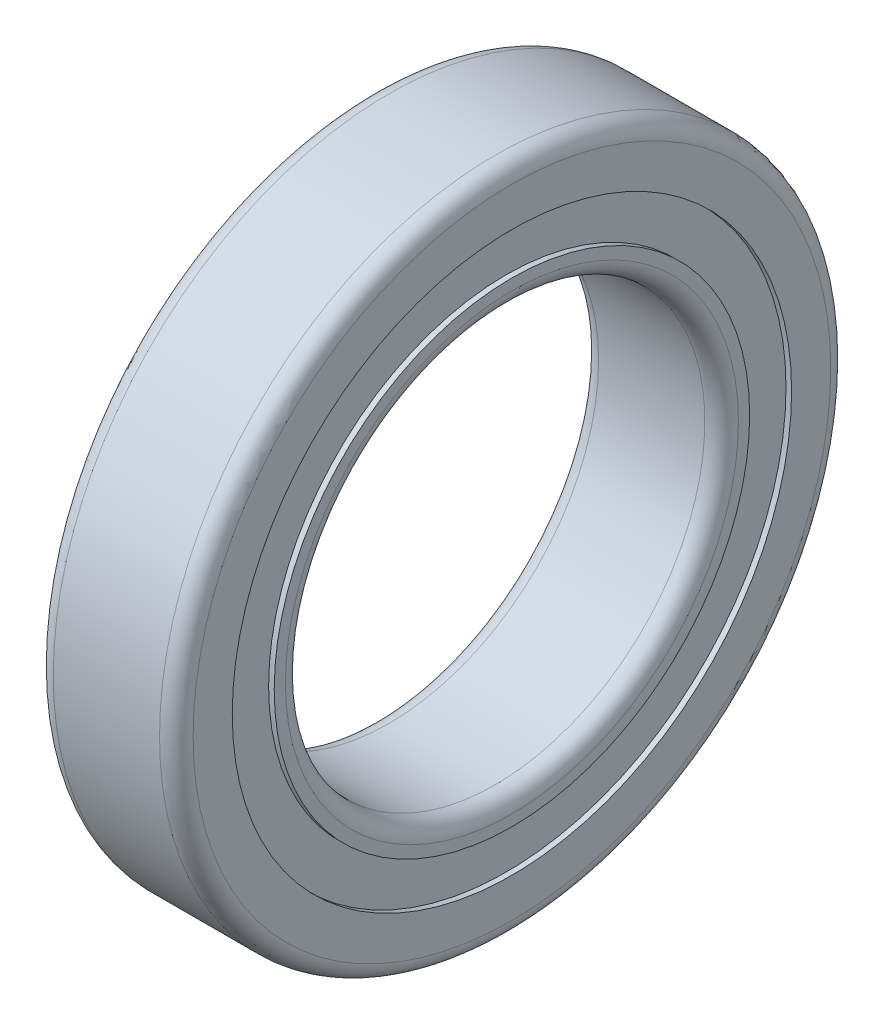
SolidWorks part; units mm, degrees
material "Plain Carbon Steel"
ref_plane "Front Plane" through (0, 0, 0) normal (0, 0, 1) x (1, 0, 0)
ref_plane "Top Plane" through (0, 0, 0) normal (0, 1, 0) x (1, 0, 0)
ref_plane "Right Plane" through (0, 0, 0) normal (1, 0, 0) x (0, 0, -1)
sketch "Sketch1" plane through (0, 0, 0) normal (0, 0, 1) x (1, 0, 0)
  line L0 (0, 0) -> (8.8933, 0) construction
  line L1 (0, 8.5) -> (0, 7.5)
  line L2 (0, 7.5) -> (5, 7.5)
  line L3 (5, 7.5) -> (5, 8.5)
  line L4 (5, 8.5) -> (4.8, 8.5)
  line L5 (4.8, 8.5) -> (4.8, 10)
  line L6 (4.8, 10) -> (5, 10)
  line L7 (5, 10) -> (5, 12)
  line L8 (5, 12) -> (0, 12)
  line L9 (0, 12) -> (0, 10)
  line L10 (0, 10) -> (0.2, 10)
  line L11 (0.2, 10) -> (0.2, 8.5)
  line L12 (0.2, 8.5) -> (0, 8.5)
  dimension "D1" = 15
  dimension "D2" = 24
  dimension "D3" = 20
  dimension "D4" = 17
  dimension "D5" = 0.2
  dimension "D6" = 5
revolve "Revolve1" add sketch "Sketch1" angle 360 about L0
fillet "Fillet1" radius 0.6 4 edges at (0, 0, 7.5) (5, 0, 7.5) (5, 0, 12) (0, 0, 12)
